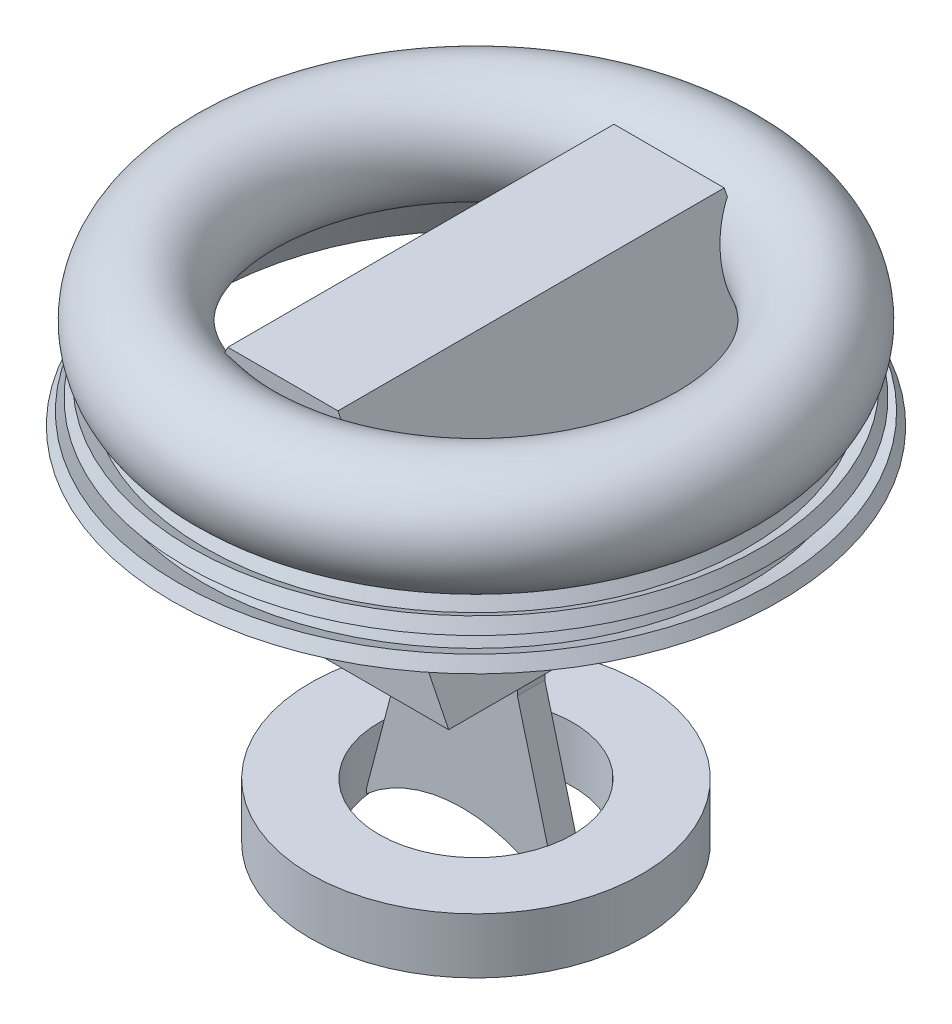
SolidWorks part; units mm, degrees
ref_plane "Alzado" through (0, 0, 0) normal (0, 0, 1) x (1, 0, 0)
ref_plane "Planta" through (0, 0, 0) normal (0, 1, 0) x (1, 0, 0)
ref_plane "Vista lateral" through (0, 0, 0) normal (1, 0, 0) x (0, 0, -1)
sketch "Croquis1" plane through (0, 0, 0) normal (0, 1, 0) x (1, 0, 0)
  line L0 (0, 87.5309) -> (0, -87.5309) construction
  line L1 (-201.3211, 0) -> (201.3211, 0) construction
  circle A0 centre (0, 0) radius 200
  circle A1 centre (0, 0) radius 117
  point P5 (0, 0)
  point P6 (0, 0)
  dimension "D1" = 400
extrude "Saliente-Extruir1" add sketch "Croquis1" along normal blind 67
sketch "Croquis2" plane through (0, 0, 0) normal (0, 0, 1) x (1, 0, 0)
  line L6 (99.9986, 67) -> (100.0014, 67) construction
  line L7 (-117.5352, 0) -> (117.5352, 0) construction
  line L8 (-200, 0) -> (200, 0) construction
  line L9 (-117.5352, 0) -> (-66.5, 195)
  line L10 (-102.8677, 67) -> (-97.1323, 67) construction
  line L12 (200, 67) -> (-200, 67) construction
  line L13 (-66.5, 195) -> (-66.5, 334.58)
  line L14 (117.5352, 0) -> (66.5, 195)
  line L15 (66.5, 195) -> (66.5, 334.58)
  line L19 (-66.5, 334.58) -> (-16.5, 434.58)
  line L20 (16.5, 434.58) -> (66.5, 334.58)
  line L21 (-16.5, 434.58) -> (16.5, 434.58)
  arc A1 (117.5352, 0) -> (-117.5352, 0) centre (0, -132.3423) ccw
  point P2 (0, 0)
  point P3 (0, 0)
  point P24 (0, 0)
  point P28 (-100, 67)
  point P31 (100, 67)
  dimension "D3" = 354
  dimension "D5" = 133
  dimension "D6" = 139.58
  dimension "D8" = 100
sketch "Croquis3" plane through (0, 0, 0) normal (0, 0, 1) x (1, 0, 0)
  line L3 (-66.5, 601) -> (66.5, 601)
  line L7 (-66.5, 601) -> (-200, 334.576)
  line L8 (66.5, 601) -> (200, 334.576)
  line L9 (-200, 334.576) -> (200, 334.576)
  line L18 (200, 67) -> (-200, 67) construction
  point P13 (0, 0)
  point P14 (0, 0)
  dimension "D1" = 298
  dimension "D4" = 133
  dimension "D6" = 267.576
extrude "Saliente-Extruir2" add sketch "Croquis3" along normal mid plane 466
extrude "Saliente-Extruir7" add sketch "Croquis2" along normal mid plane 33 contours A1 L14 L15 L20 L21 L19 L13 L9
sketch "Croquis7" plane through (0, 0, 0) normal (0, 0, 1) x (1, 0, 0)
  line L0 (0, 634.3616) -> (0, -42.9504) construction
  line L1 (-290, 546) -> (290, 546) construction
  line L2 (-343.934, 480.1871) -> (-370.2666, 428.5065) construction
  line L3 (-200, 0) -> (200, 0) construction
  line L4 (-328.568, 435.3209) -> (-358.9157, 450.7839)
  line L5 (-290, 666.6146) -> (-290, 469.9588) construction
  line L6 (290, 666.6146) -> (290, 469.9588) construction
  line L7 (-279.3697, 566.8632) -> (-328.4585, 470.5209) construction
  line L8 (-320.1904, 486.7481) -> (-327.6826, 472.0438)
  line L9 (-372.1248, 587.1512) -> (-63.8478, 432.6794) construction
  line L10 (-66.5, 601) -> (-200, 334.576) construction
  line L11 (-327.6826, 472.0438) -> (-343.934, 480.1871)
  line L12 (-343.934, 480.1871) -> (-351.5501, 464.9879)
  line L13 (-351.5501, 464.9879) -> (-321.2982, 449.8292)
  line L14 (-321.2982, 449.8292) -> (-328.568, 435.3209)
  line L18 (-321.1922, 412.4832) -> (-286.7043, 479.5817)
  line L19 (-321.1922, 412.4832) -> (-366.6336, 435.6367)
  line L20 (-366.6336, 435.6367) -> (-358.9157, 450.7839)
  circle A0 centre (-290, 546) radius 50
  arc A1 (-286.7043, 479.5817) -> (-320.1904, 486.7481) centre (-290, 546) ccw
  point P7 (0, 546)
  dimension "D4" = 100
  dimension "D5" = 133
  dimension "D1" = 546
  dimension "D2" = 580
  dimension "D3" = 27
  dimension "D6" = 90
  dimension "D7" = 33
  dimension "D8" = 17
  dimension "D9" = 17
  dimension "D10" = 33
  dimension "D11" = 50
  dimension "D12" = 133
  dimension "D13" = 51
revolve "Revolución1" add sketch "Croquis7" angle 360 about L0
